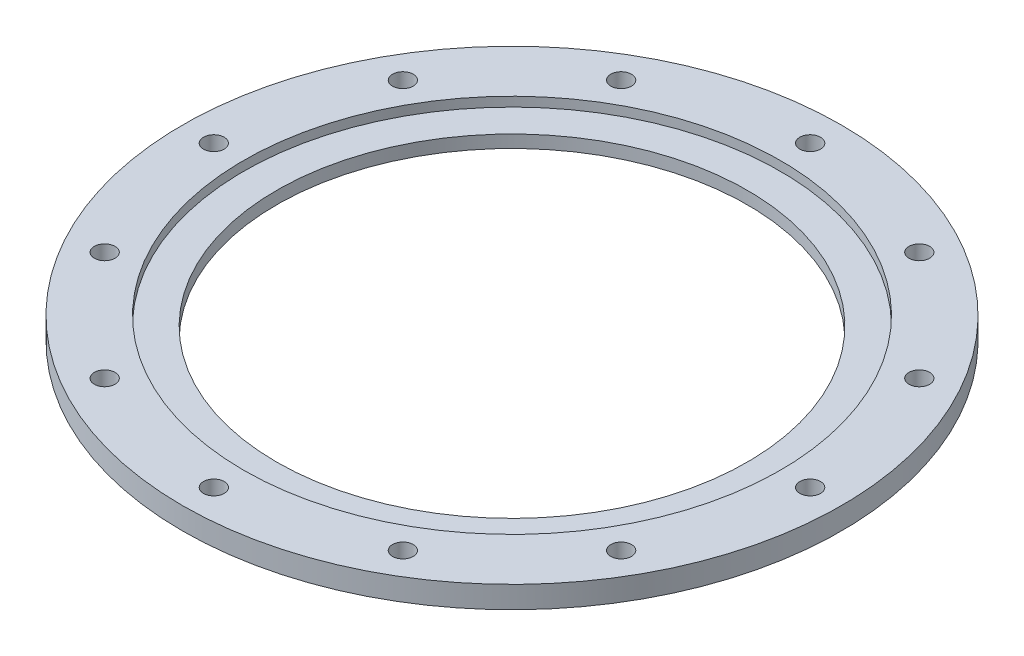
SolidWorks part; units mm, degrees
ref_plane "Front Plane" through (0, 0, 0) normal (0, 0, 1) x (1, 0, 0)
ref_plane "Top Plane" through (0, 0, 0) normal (0, 1, 0) x (1, 0, 0)
ref_plane "Right Plane" through (0, 0, 0) normal (1, 0, 0) x (0, 0, -1)
sketch "Sketch1" plane through (0, 0, 0) normal (0, 1, 0) x (1, 0, 0)
  circle A0 centre (0, 0) radius 37.5
  circle A1 centre (0, 0) radius 52.5
  dimension "D1" = 15
  dimension "D2" = 75
extrude "Boss-Extrude1" add sketch "Sketch1" along normal blind 2
sketch "Sketch2" plane through (0, 2, 0) normal (0, 1, 0) x (1, 0, 0)
  circle A0 centre (0, 0) radius 42.75
  circle A1 centre (0, 0) radius 52.5 construction
  circle A2 centre (0, 0) radius 52.5
  dimension "D1" = 85.5
extrude "Boss-Extrude2" add sketch "Sketch2" along normal blind 1.5
sketch "Sketch3" plane through (0, 0, 0) normal (0, -1, 0) x (1, 0, 0)
  line L0 (0, 0) -> (47.5, 0) construction
  circle A0 centre (0, 0) radius 47.5 construction
  circle A1 centre (0, 0) radius 52.5 construction
  circle A2 centre (47.5, 0) radius 1.65
  dimension "D1" = 5
  dimension "D2" = 3.3
extrude "Cut-Extrude1" cut sketch "Sketch3" against normal through all
pattern_circular "CirPattern1" count 12 over 360 about axis through (0, 0, 0) along (0, 1, 0) of "Cut-Extrude1"
